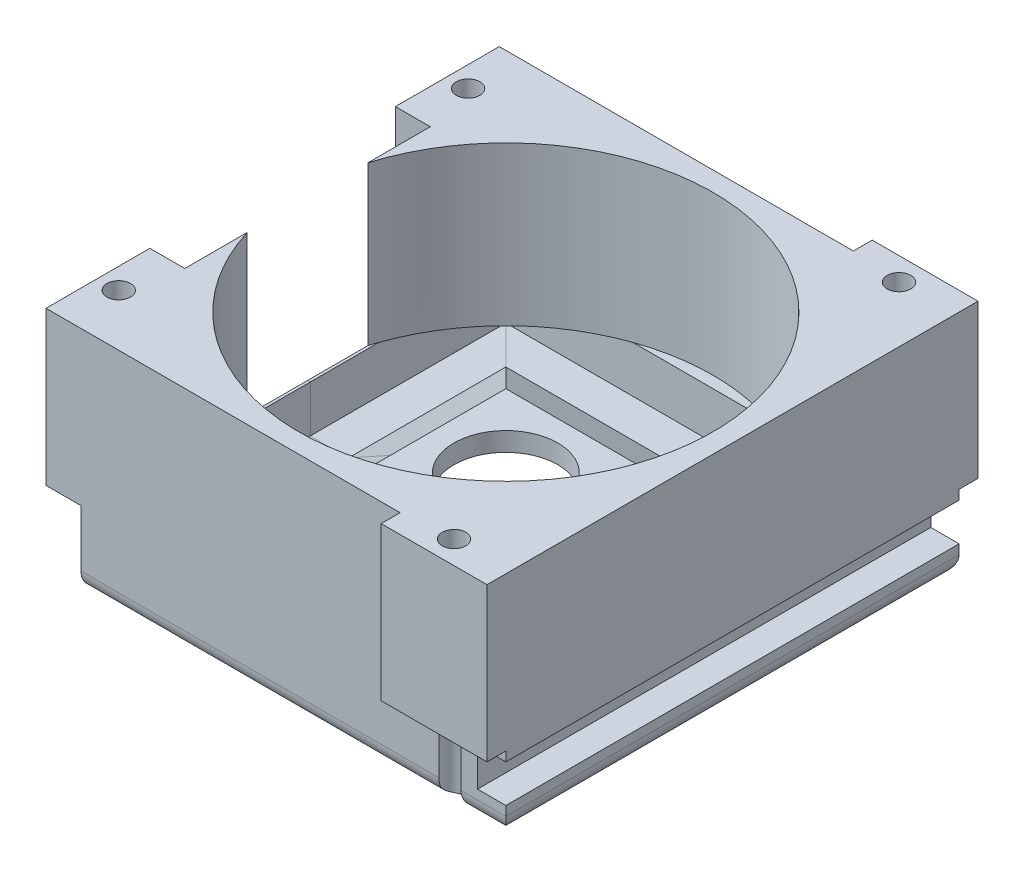
SolidWorks part; units mm, degrees
ref_plane "前基準面" through (0, 0, 0) normal (0, 0, 1) x (1, 0, 0)
ref_plane "上基準面" through (0, 0, 0) normal (0, 1, 0) x (1, 0, 0)
ref_plane "右基準面" through (0, 0, 0) normal (1, 0, 0) x (0, 0, -1)
sketch "草圖1" plane through (0, 0, 0) normal (0, 1, 0) x (1, 0, 0)
  circle A0 centre (0, 0) radius 48
  circle A1 centre (0, 0) radius 42
  dimension "D1" = 84
  dimension "D2" = 96
ref_plane "平面1" through (0, 0, 0) normal (0, 1, 0) x (1, 0, 0)
ref_plane "平面2" through (0, 30, 0) normal (0, 1, 0) x (1, 0, 0)
sketch "草圖2" plane through (0, 30, 0) normal (0, 1, 0) x (1, 0, 0)
  circle A0 centre (0, 0) radius 13.3695
  circle A1 centre (0, 0) radius 48
sketch "草圖5" plane through (0, 0, 0) normal (1, 0, 0) x (0, 0, -1)
  line L0 (0, 30) -> (0, 0)
  line L1 (48, 30) -> (-48, 30) construction
  line L2 (48, 0) -> (-48, 0) construction
  line L3 (-43.6204, 0) -> (-49.6204, 0)
  line L4 (-49.6204, 0) -> (-49.6204, 30)
  line L5 (-49.6204, 30) -> (-13.6204, 30)
  spline S0 degree 3 poles (-13.6204, 30) (-13.0085, 14.2456) (-29.9808, 2.9583) (-43.6204, 0) knots 0 0 0 0 1 1 1 1
  dimension "D1" = 36
  dimension "D2" = 6
revolve "旋轉1" [suppressed] add sketch "草圖5" angle 360 about L0
sketch "草圖6" plane through (0, 0, 0) normal (0, 1, 0) x (1, 0, 0)
  line L1 (-42, 42) -> (42, 42)
  line L2 (-42, 42) -> (-42, -42)
  line L3 (-42, -42) -> (42, -42)
  line L4 (42, 42) -> (42, -42)
  line L5 (-42, 42) -> (42, -42) construction
  line L6 (-42, -42) -> (42, 42) construction
  line L7 (-48, 48) -> (48, 48)
  line L8 (-48, 48) -> (-48, -48)
  line L9 (-48, -48) -> (48, -48)
  line L10 (48, 48) -> (48, -48)
  line L11 (-48, 48) -> (48, -48) construction
  line L12 (-48, -48) -> (48, 48) construction
  point P0 (0, 0)
  point P6 (0, 0)
  dimension "D1" = 84
  dimension "D2" = 84
  dimension "D3" = 96
  dimension "D4" = 96
sketch "草圖7" plane through (0, 0, 0) normal (0, 0, 1) x (1, 0, 0)
  line L0 (-48, 0) -> (-48, 14.9628)
  line L1 (48, 0) -> (-48, 0) construction
  line L2 (-48, 0) -> (48, 0) construction
  line L3 (-11, 15) -> (-15.4535, 15)
  line L5 (-48, 0) -> (-42, 0)
  line L6 (42, 0) -> (-42, 0) construction
  line L7 (-15.4535, 15) -> (-33.3508, 5.0745)
  line L8 (-48, 14.9628) -> (-41.4277, 14.9628)
  line L9 (-41.4277, 14.9628) -> (-41.4277, 5.0745)
  line L10 (-41.4277, 5.0745) -> (-33.3508, 5.0745)
  line L12 (-11, 15) -> (-11, 0) construction
  line L13 (-11, 0) -> (-42, 0) construction
  line L14 (-11, 15) -> (-48, 15) construction
  spline S0 degree 3 poles (-11, 15) (-19.9624, 7.7836) (-30.4466, 1.6529) (-42, 0) knots 0 0 0 0 1 1 1 1
  dimension "D1" = 15
  dimension "D2" = 11
  dimension "D3" = 48
sweep "掃出1" add profiles "草圖7" path "草圖6"
ref_plane "平面3" through (0, 14.9628, 0) normal (0, 1, 0) x (1, 0, 0)
sketch "草圖8" plane through (0, 14.9628, 0) normal (0, 1, 0) x (1, 0, 0)
  line L1 (-48, 48) -> (48, 48)
  line L2 (-48, 48) -> (-48, -48)
  line L3 (-48, -48) -> (48, -48)
  line L4 (48, 48) -> (48, -48)
  line L5 (-48, 48) -> (48, -48) construction
  line L6 (-48, -48) -> (48, 48) construction
  circle A0 centre (0, 0) radius 43.9
  dimension "D1" = 87.8
extrude "填料-伸長1" add sketch "草圖8" along normal blind 33.54
sketch "草圖14" plane through (0, 0, 0) normal (0, 1, 0) x (1, 0, 0)
  line L0 (-48, -48) -> (48, -48) construction
  line L1 (-48, 48) -> (-42, 48)
  line L2 (-48, 48) -> (-48, -48)
  line L3 (-48, -48) -> (-42, -48)
  line L4 (-42, 48) -> (-42, -48)
  dimension "D1" = 6
extrude "除料-伸長3" cut sketch "草圖14" against normal blind 8.53 and the other way through all
sketch "草圖15" plane through (0, 0, 0) normal (0, 1, 0) x (1, 0, 0)
  line L0 (-42, -48) -> (48, -48) construction
  line L1 (-42, 48) -> (-33.3508, 48)
  line L2 (-42, 48) -> (-42, -48)
  line L3 (-42, -48) -> (-33.3508, -48)
  line L4 (-33.3508, 48) -> (-33.3508, -48)
sketch "草圖16" plane through (0, 30, 0) normal (0, 1, 0) x (1, 0, 0)
  line L0 (0, 0) -> (63.4478, 0) construction
  line L1 (48, 48) -> (25.6, 48)
  line L2 (48, 48) -> (48, 52)
  line L3 (48, 52) -> (25.6, 52)
  line L4 (25.6, 48) -> (25.6, 52)
  line L5 (48, -52) -> (25.6, -52)
  line L6 (25.6, -48) -> (25.6, -52)
  line L7 (48, -48) -> (25.6, -48)
  line L8 (48, -48) -> (48, -52)
  line L9 (-42, -26) -> (-49.4, -26)
  line L10 (-42, 48) -> (-49.4, 48)
  line L11 (-42, 48) -> (-42, 26)
  line L12 (-42, 26) -> (-49.4, 26)
  line L13 (-49.4, 48) -> (-49.4, 26)
  line L14 (-49.4, -48) -> (-49.4, -26)
  line L15 (-42, -48) -> (-49.4, -48)
  line L16 (-42, -48) -> (-42, -26)
  circle A0 centre (-45, 37) radius 2.5
  circle A5 centre (-45, -37) radius 2.5
  dimension "D5" = 5
  dimension "D1" = 25.6
  dimension "D2" = 4
  dimension "D3" = 26
  dimension "D4" = 7.4
  dimension "D6" = 37
  dimension "D7" = 45
extrude "填料-伸長3" add sketch "草圖16" along normal up to surface (18.5028 mm away) and the other way blind 14 up to face at (2.3167, 48.5028, 0)
fillet "圓角5" radius 4 3 edges at (3, 0, -48) (48, 0, 0) (3, 0, 48)
ref_plane "平面4" through (0, 0, 48) normal (0, 0, 1) x (1, 0, 0)
sketch "草圖17" plane through (0, 0, 48) normal (0, 0, 1) x (1, 0, 0)
  line L0 (-49.4, 48.5028) -> (-49.4, 0)
sketch "草圖18" plane through (48, 0, 0) normal (1, 0, 0) x (0, 0, -1)
  line L0 (-52, 48.5028) -> (-52, 0)
sketch "草圖20" plane through (48, 0, 0) normal (1, 0, 0) x (0, 0, -1)
  line L0 (-52, 48.5028) -> (-52, 0)
ref_plane "平面5" through (0, 15, 0) normal (0, 1, 0) x (1, 0, 0)
sketch "草圖21" plane through (0, 15, 0) normal (0, 1, 0) x (1, 0, 0)
  line L1 (-15.4535, 15.4535) -> (15.4535, 15.4535)
  line L2 (-15.4535, 15.4535) -> (-15.4535, -15.4535)
  line L3 (-15.4535, -15.4535) -> (15.4535, -15.4535)
  line L4 (15.4535, 15.4535) -> (15.4535, -15.4535)
  circle A0 centre (0, 0) radius 11
extrude "填料-伸長4" add sketch "草圖21" along normal blind 4
sketch "草圖22" plane through (0, 48.5028, 0) normal (0, 1, 0) x (1, 0, 0)
  line L0 (0, 0) -> (48, 0) construction
  line L1 (48, -52) -> (48, 52) construction
  circle A0 centre (36.1427, 47.1225) radius 2.5
  circle A1 centre (36.1427, -47.1225) radius 2.5
  dimension "D1" = 5
extrude "除料-伸長4" cut sketch "草圖22" against normal through all
ref_plane "平面6" through (0, 0, -52) normal (0, 0, -1) x (-1, 0, 0)
sketch "草圖23" plane through (0, 0, -52) normal (0, 0, -1) x (-1, 0, 0)
  line L0 (-48, 16) -> (-48, 48.5028) construction
  line L1 (-48, 14) -> (-42, 14)
  line L2 (-48, 14) -> (-48, 6)
  line L3 (-48, 6) -> (-42, 6)
  line L4 (-42, 14) -> (-42, 6)
  line L5 (-48, 4) -> (-38.4836, 4) construction
  line L6 (-48, 4) -> (-48, 16) construction
  dimension "D1" = 2
  dimension "D2" = 10
  dimension "D3" = 6
extrude "除料-伸長5" cut sketch "草圖23" against normal through all both and the other way through all
